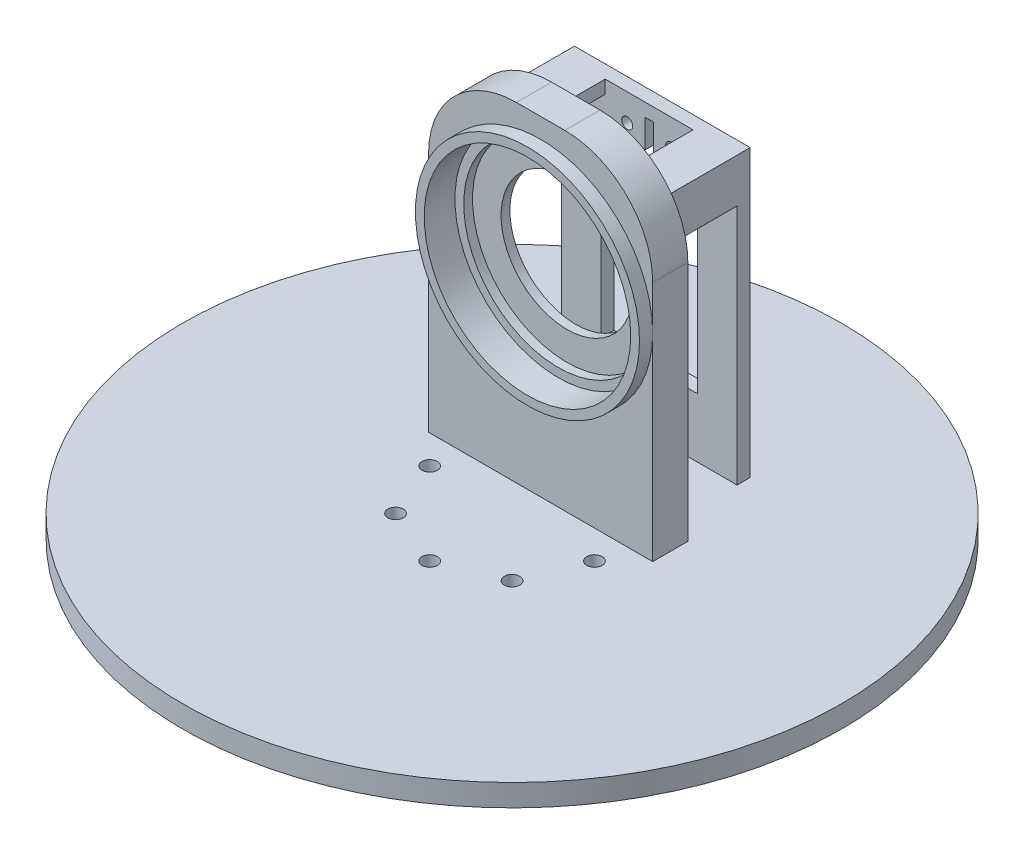
SolidWorks part; units mm, degrees
ref_plane "정면" through (0, 0, 0) normal (0, 0, 1) x (1, 0, 0)
ref_plane "윗면" through (0, 0, 0) normal (0, 1, 0) x (1, 0, 0)
ref_plane "우측면" through (0, 0, 0) normal (1, 0, 0) x (0, 0, -1)
sketch "스케치1" plane through (0, 0, 0) normal (0, 0, 1) x (1, 0, 0)
  circle A0 centre (0, 0) radius 25.5
  circle A1 centre (0, 0) radius 15
  dimension "D1" = 51
  dimension "D2" = 30
extrude "보스-돌출1" add sketch "스케치1" along normal blind 2
sketch "스케치2" plane through (0, 0, 2) normal (0, 0, 1) x (1, 0, 0)
  circle A0 centre (0, 0) radius 25.5
  circle A1 centre (0, 0) radius 21.5
  dimension "D1" = 4
extrude "보스-돌출2" add sketch "스케치2" along normal blind 2
sketch "스케치3" plane through (0, 0, 4) normal (0, 0, 1) x (1, 0, 0)
  circle A0 centre (0, 0) radius 25.5
  circle A1 centre (0, 0) radius 23.5
  dimension "D1" = 2
extrude "보스-돌출3" add sketch "스케치3" along normal blind 7
sketch "스케치4" plane through (0, 0, 0) normal (0, 0, -1) x (-1, 0, 0)
  line L0 (-25.5, 30) -> (25.5, 30)
  line L1 (-25.5, -50) -> (25.5, -50)
  line L2 (-25.5, -50) -> (-25.5, 30)
  line L4 (25.5, -50) -> (25.5, 30)
  circle A0 centre (0, 0) radius 25.5 construction
  circle A3 centre (0, 0) radius 23.5
  point P0 (0, 0)
  dimension "D2" = 30
  dimension "D1" = 80
extrude "보스-돌출4" add sketch "스케치4" against normal blind 8
fillet "필렛1" radius 20 2 edges at (25.5, 30, 4) (-25.5, 30, 4)
sketch "스케치5" plane through (0, 0, 0) normal (0, 0, -1) x (-1, 0, 0)
  line L0 (-20, 20) -> (20, -40) construction
  line L1 (-20, -40) -> (20, -40) construction
  line L2 (-20, -40) -> (-20, 20) construction
  line L3 (-20, 20) -> (20, 20) construction
  line L4 (20, -40) -> (20, 20) construction
  line L5 (-20, -40) -> (20, 20) construction
  line L6 (0, 30) -> (0, -50) construction
  line L7 (5.5, 30) -> (-5.5, 30) construction
  line L8 (-25.5, -50) -> (25.5, -50) construction
  line L9 (25.5, -50) -> (25.5, 10) construction
  line L10 (-20, 20) -> (-10, 20)
  line L12 (-17, 17) -> (-10, 17)
  line L13 (-10, 20) -> (-10, 17)
  line L14 (20, 20) -> (10, 20)
  line L16 (17, 17) -> (10, 17)
  line L17 (10, 20) -> (10, 17)
  line L26 (-25.5, -50) -> (25.5, -50)
  line L27 (-25.5, -50) -> (-25.5, -45)
  line L28 (-25.5, -45) -> (25.5, -45)
  line L29 (25.5, -50) -> (25.5, -45)
  line L32 (-20, 20) -> (-20, 10)
  line L33 (-20, 10) -> (-17, 10)
  line L34 (-17, 17) -> (-17, 10)
  line L36 (20, 20) -> (20, 10)
  line L37 (20, 10) -> (17, 10)
  line L38 (17, 17) -> (17, 10)
  circle A0 centre (0, 0) radius 15 construction
  point P12 (0, -10)
  dimension "D1" = 20
  dimension "D2" = 60
  dimension "D3" = 40
  dimension "D5" = 3
  dimension "D6" = 5
  dimension "D7" = 3
extrude "보스-돌출5" add sketch "스케치5" along normal blind 19.7
sketch "스케치6" plane through (0, 0, -19.7) normal (0, 0, -1) x (-1, 0, 0)
  line L0 (-25.5, -50) -> (25.5, -50) construction
  line L1 (-20, -50) -> (20, -50)
  line L2 (-20, -50) -> (-20, 20)
  line L3 (-20, 20) -> (20, 20)
  line L4 (20, -50) -> (20, 20)
extrude "보스-돌출6" add sketch "스케치6" against normal blind 3
sketch "스케치7" plane through (0, 0, -19.7) normal (0, 0, -1) x (-1, 0, 0)
  line L0 (20, 20) -> (-20, 20) construction
  line L1 (-11, -31.5) -> (-1, -31.5)
  line L2 (-11, -31.5) -> (-11, 10.5)
  line L3 (-11, 10.5) -> (-1, 10.5)
  line L4 (11, -31.5) -> (11, 10.5)
  line L5 (-11, -31.5) -> (11, 10.5) construction
  line L6 (-11, 10.5) -> (11, -31.5) construction
  line L7 (0, 20) -> (0, -50) construction
  line L8 (-25.5, -50) -> (25.5, -50) construction
  line L9 (1, -31.5) -> (11, -31.5)
  line L10 (-5, 13.85) -> (5, 13.85) construction
  line L11 (-5, 13.85) -> (-5, -34.75) construction
  line L12 (-5, -34.75) -> (5, -34.75) construction
  line L13 (5, 13.85) -> (5, -34.75) construction
  line L14 (-5, 13.85) -> (5, -34.75) construction
  line L15 (-5, -34.75) -> (5, 13.85) construction
  line L16 (1, 17) -> (-1, 17)
  line L17 (1, 17) -> (1, 10.5)
  line L19 (-1, 17) -> (-1, 10.5)
  line L20 (1, 17) -> (-1, 10.5) construction
  line L21 (1, 10.5) -> (-1, 17) construction
  line L22 (-1, -38) -> (1, -38)
  line L23 (-1, -38) -> (-1, -31.5)
  line L25 (1, -38) -> (1, -31.5)
  line L26 (-1, -38) -> (1, -31.5) construction
  line L27 (-1, -31.5) -> (1, -38) construction
  line L28 (1, 10.5) -> (11, 10.5)
  circle A0 centre (-5, 13.85) radius 1.25
  circle A1 centre (5, 13.85) radius 1.25
  circle A2 centre (5, -34.75) radius 1.25
  circle A3 centre (-5, -34.75) radius 1.25
  point P0 (0, -10.5)
  point P12 (0, -10.45)
  point P20 (0, 13.75)
  point P25 (0, -34.75)
  dimension "D7" = 2.5
  dimension "D1" = 22
  dimension "D2" = 42
  dimension "D3" = 9.5
  dimension "D4" = 10
  dimension "D5" = 3.35
  dimension "D6" = 3.25
  dimension "D8" = 2
  dimension "D9" = 6.5
  dimension "D10" = 2
  dimension "D11" = 6.5
extrude "컷-돌출1" cut sketch "스케치7" against normal up to next
sketch "스케치8" plane through (0, -50, 0) normal (0, -1, 0) x (1, 0, 0)
  line L0 (25.5, 8) -> (-25.5, 8) construction
  circle A0 centre (0, 14.5) radius 75
  dimension "D2" = 150
  dimension "D1" = 6.5
extrude "보스-돌출7" add sketch "스케치8" against normal blind 5
sketch "스케치9" plane through (0, -50, 0) normal (0, -1, 0) x (1, 0, 0)
  circle A0 centre (0, 14.5) radius 22.5
  dimension "D1" = 45
extrude "컷-돌출2" cut sketch "스케치9" against normal blind 2
sketch "스케치10" plane through (0, -48, 0) normal (0, -1, 0) x (1, 0, 0)
  circle A0 centre (0, 14.5) radius 18.75 construction
  circle A1 centre (0, 33.25) radius 1.75
  circle A9 centre (13.2583, 27.7583) radius 1.75
  circle A10 centre (18.75, 14.5) radius 1.75
  circle A12 centre (0, -4.25) radius 1.75
  circle A14 centre (-18.75, 14.5) radius 1.75
  circle A15 centre (-13.2583, 27.7583) radius 1.75
  circle A16 centre (13.2583, 1.2417) radius 1.75 [skipped]
  circle A17 centre (-13.2583, 1.2417) radius 1.75 [skipped]
  point P20 (0, 14.5)
  point P22 (0, 14.5)
  dimension "D1" = 37.5
  dimension "D2" = 3.5
  dimension "D3" = 8
extrude "컷-돌출3" cut sketch "스케치10" against normal up to next
